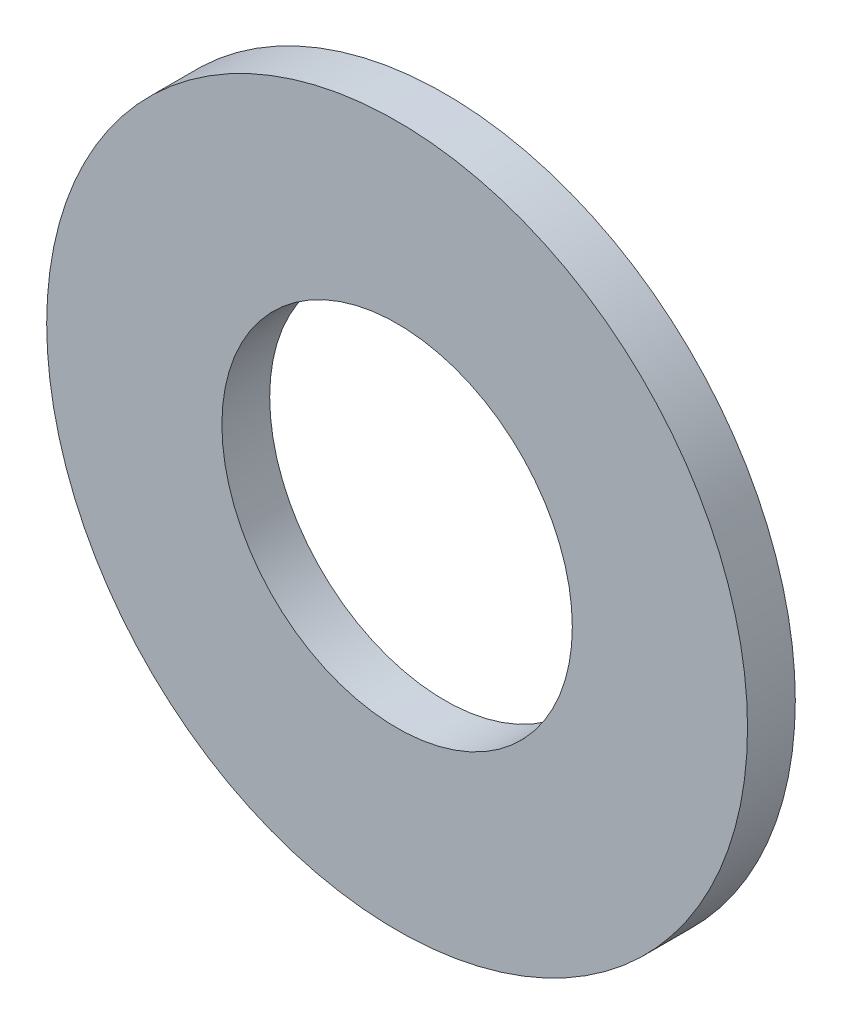
SolidWorks part; units mm, degrees
material "2A12"
ref_plane "前视基准面" through (0, 0, 0) normal (0, 0, 1) x (1, 0, 0)
ref_plane "上视基准面" through (0, 0, 0) normal (0, 1, 0) x (1, 0, 0)
ref_plane "右视基准面" through (0, 0, 0) normal (1, 0, 0) x (0, 0, -1)
sketch "Sketch1" plane through (0, 0, 0) normal (0, 0, 1) x (1, 0, 0)
  circle A0 centre (0, 0) radius 11
  circle A1 centre (0, 0) radius 5.5
  dimension "D1" = 11
  dimension "D2" = 22
extrude "Extrude1" add sketch "Sketch1" along normal blind 1.5
